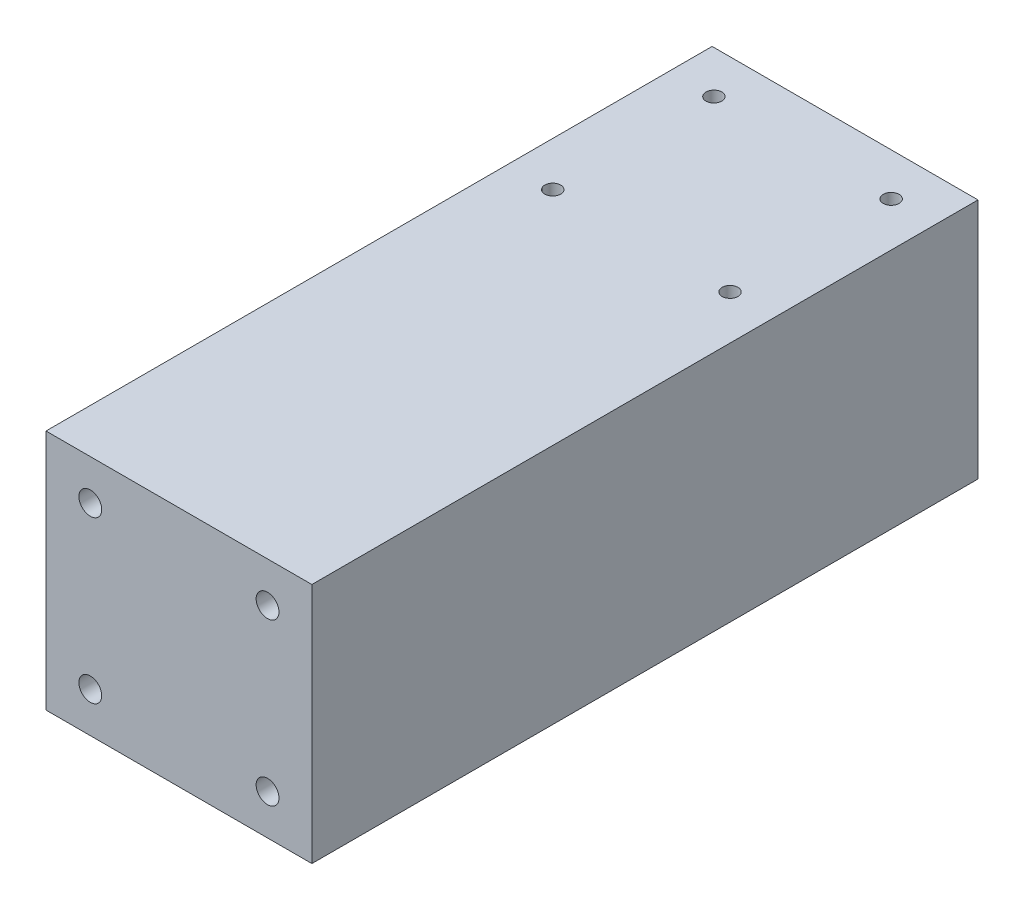
SolidWorks part; units mm, degrees
ref_plane "Front Plane" through (0, 0, 0) normal (0, 0, 1) x (1, 0, 0)
ref_plane "Top Plane" through (0, 0, 0) normal (0, 1, 0) x (1, 0, 0)
ref_plane "Right Plane" through (0, 0, 0) normal (1, 0, 0) x (0, 0, -1)
sketch "Sketch2" plane through (0, 0, 0) normal (0, 0, 1) x (1, 0, 0)
  line L0 (0, 0) -> (0, -38.1) construction
  line L3 (-20.955, -19.05) -> (20.955, -19.05) construction
  line L6 (-13.97, -6.35) -> (-13.97, -31.75) construction
  line L7 (-6.985, 0) -> (-6.985, -38.1) construction
  line L8 (6.985, 0) -> (6.985, -38.1) construction
  line L15 (20.955, 0) -> (-20.955, 0) construction
  line L16 (-20.955, 0) -> (-20.955, -38.1) construction
  line L17 (-20.955, -38.1) -> (20.955, -38.1) construction
  line L18 (20.955, -38.1) -> (20.955, 0) construction
  circle A0 centre (-13.97, -6.35) radius 1
  circle A1 centre (13.97, -6.35) radius 1
  circle A2 centre (-13.97, -31.75) radius 1
  circle A3 centre (13.97, -31.75) radius 1
  circle A4 centre (0, -19.05) radius 1
  point P0 (-13.97, -6.35)
  point P32 (-13.97, -6.35)
  dimension "D3" = 2
  dimension "D4" = 2
  dimension "D1" = 27.94
  dimension "D2" = 25.4
sketch "Sketch3" plane through (0, 0, 0) normal (0, 0, 1) x (1, 0, 0)
  line L1 (0, 0) -> (20.955, 0)
  line L2 (0, 0) -> (0, -38.1)
  line L3 (0, -38.1) -> (20.955, -38.1)
  line L4 (20.955, 0) -> (20.955, -38.1)
  line L5 (0, 0) -> (-20.955, 0)
  line L6 (0, 0) -> (0, -38.1)
  line L7 (0, -38.1) -> (-20.955, -38.1)
  line L8 (-20.955, 0) -> (-20.955, -38.1)
extrude "Boss-Extrude1" add sketch "Sketch3" along normal blind 5 contours L4 L1 L2 L3 | L5 L8 L7 L2
hole_wizard "CSK for M3 Countersunk Flat Head Screw1" positions "Sketch2" profile "Sketch4" countersink size "M3" standard "ISO"
sketch "Sketch4" plane through (-13.97, -6.35, 0) normal (1, 0, 0) x (0, 1, 0)
  line L0 (0, 0) -> (0, 11.0815)
  line L1 (0, 11.0815) -> (1.8, 10)
  line L2 (1.8, 10) -> (1.8, 1.35)
  line L3 (1.8, 1.35) -> (3.15, 0)
  line L5 (3.15, 0) -> (0, 0)
  line L6 (-1.8, 1.35) -> (-3.15, 0) construction
  line L10 (0, 11.0815) -> (-1.8, 10) construction
  line L11 (0, -6.35) -> (0, 107.95) construction
  dimension "Hole Dia." = 3.6
  dimension "Hole Depth" = 10
  dimension "Near C'Sink Dia." = 6.3
  dimension "Near C'Sink Angle" = 90
  dimension "Drill Angle" = 118
sketch "Sketch7" plane through (0, 0, 0) normal (0, 0, 1) x (1, 0, 0)
  line L0 (0, 0) -> (0, -38.1) construction
  line L3 (-20.955, -19.05) -> (20.955, -19.05) construction
  line L6 (-13.97, -6.35) -> (-13.97, -31.75) construction
  line L7 (-6.985, 0) -> (-6.985, -38.1) construction
  line L8 (6.985, 0) -> (6.985, -38.1) construction
  line L15 (20.955, 0) -> (-20.955, 0) construction
  line L16 (-20.955, 0) -> (-20.955, -38.1) construction
  line L17 (-20.955, -38.1) -> (20.955, -38.1) construction
  line L18 (20.955, -38.1) -> (20.955, 0) construction
  circle A0 centre (-13.97, -6.35) radius 1
  circle A1 centre (13.97, -6.35) radius 1
  circle A2 centre (-13.97, -31.75) radius 1
  circle A3 centre (13.97, -31.75) radius 1
  circle A4 centre (0, -19.05) radius 1
  point P0 (-13.97, -6.35)
  point P2 (13.97, -6.35)
  point P4 (-13.97, -31.75)
  point P6 (13.97, -31.75)
  point P32 (-13.97, -6.35)
  point P39 (-13.97, -31.75)
  dimension "D3" = 2
  dimension "D4" = 2
  dimension "D1" = 27.94
  dimension "D2" = 25.4
hole_wizard "CSK for M3 Countersunk Flat Head Screw2" positions "Sketch7" profile "Sketch8" countersink size "M3" standard "ISO"
sketch "Sketch8" plane through (-13.97, -31.75, 0) normal (1, 0, 0) x (0, 1, 0)
  line L0 (0, 0) -> (0, 11.0815)
  line L1 (0, 11.0815) -> (1.8, 10)
  line L2 (1.8, 10) -> (1.8, 1.35)
  line L3 (1.8, 1.35) -> (3.15, 0)
  line L5 (3.15, 0) -> (0, 0)
  line L6 (-1.8, 1.35) -> (-3.15, 0) construction
  line L10 (0, 11.0815) -> (-1.8, 10) construction
  line L11 (0, -6.35) -> (0, 107.95) construction
  dimension "Hole Dia." = 3.6
  dimension "Hole Depth" = 10
  dimension "Near C'Sink Dia." = 6.3
  dimension "Near C'Sink Angle" = 90
  dimension "Drill Angle" = 118
sketch "Sketch12" plane through (0, 0, 0) normal (0, 0, -1) x (-1, 0, 0)
  line L0 (-20.955, 0) -> (-20.955, -38.1) construction
  line L1 (-20.955, 0) -> (20.955, 0)
  line L2 (-20.955, 0) -> (-20.955, -38.1)
  line L3 (-20.955, -38.1) -> (20.955, -38.1)
  line L4 (20.955, 0) -> (20.955, -38.1)
extrude "Boss-Extrude2" add sketch "Sketch12" along normal blind 100
sketch "Sketch15" plane through (0, 0, -100) normal (0, 0, -1) x (-1, 0, 0)
  line L1 (-17.7293, -2.7034) -> (17.7293, -2.7034)
  line L2 (-17.7293, -2.7034) -> (-17.7293, -35.2451)
  line L3 (-17.7293, -35.2451) -> (17.7293, -35.2451)
  line L4 (17.7293, -2.7034) -> (17.7293, -35.2451)
  line L5 (-17.7293, -2.7034) -> (17.7293, -35.2451) construction
  line L6 (-17.7293, -35.2451) -> (17.7293, -2.7034) construction
  point P0 (0, -18.9742)
  point P5 (0, 0)
  point P6 (0, 0)
  point P7 (0, 0)
  point P8 (0, -19.2773)
  point P9 (17.7483, -3.2527)
  point P10 (0, 0)
  point P11 (17.7104, -2.192)
  point P12 (17.7104, -2.7602)
  point P13 (0, 0)
  point P14 (0, 0)
  point P15 (17.8241, -35.3019)
  point P16 (0, -18.9742)
extrude "Cut-Extrude4" cut sketch "Sketch15" against normal blind 100
sketch "Sketch20" plane through (0, 0, 0) normal (0, -1, 0) x (1, 0, 0)
  line L0 (0, -61.5456) -> (0, -99.6456) construction
  line L3 (-20.955, -80.5956) -> (20.955, -80.5956) construction
  line L6 (-13.97, -67.8956) -> (-13.97, -93.2956) construction
  line L7 (-6.985, -61.5456) -> (-6.985, -99.6456) construction
  line L8 (6.985, -61.5456) -> (6.985, -99.6456) construction
  line L15 (20.955, -61.5456) -> (-20.955, -61.5456) construction
  line L16 (-20.955, -61.5456) -> (-20.955, -99.6456) construction
  line L17 (-20.955, -99.6456) -> (20.955, -99.6456) construction
  line L18 (20.955, -99.6456) -> (20.955, -61.5456) construction
  circle A0 centre (-13.97, -67.8956) radius 1
  circle A1 centre (13.97, -67.8956) radius 1
  circle A2 centre (-13.97, -93.2956) radius 1
  circle A3 centre (13.97, -93.2956) radius 1
  circle A4 centre (0, -80.5956) radius 1
  point P0 (-13.97, -67.8956)
  point P2 (13.97, -67.8956)
  point P4 (-13.97, -93.2956)
  point P6 (13.97, -93.2956)
  point P32 (-13.97, -67.8956)
  point P39 (-13.97, -93.2956)
  dimension "D3" = 2
  dimension "D4" = 2
  dimension "D1" = 27.94
  dimension "D2" = 25.4
hole_wizard "M3 Tapped Hole1" positions "Sketch20" profile "Sketch23" tap size "M3" standard "ISO"
sketch "Sketch23" plane through (-13.97, 0, -93.2956) normal (1, 0, 0) x (0, 0, 1)
  line L0 (0, 0) -> (0, 10.7511)
  line L1 (0, 10.7511) -> (1.25, 10)
  line L2 (1.25, 10) -> (1.25, 0)
  line L5 (1.25, 0) -> (0, 0)
  line L10 (0, 10.7511) -> (-1.25, 10) construction
  line L11 (0, -6.35) -> (0, 107.95) construction
  dimension "Tap Drill Dia." = 2.5
  dimension "Tap Drill Depth" = 10
  dimension "Drill Angle" = 118
